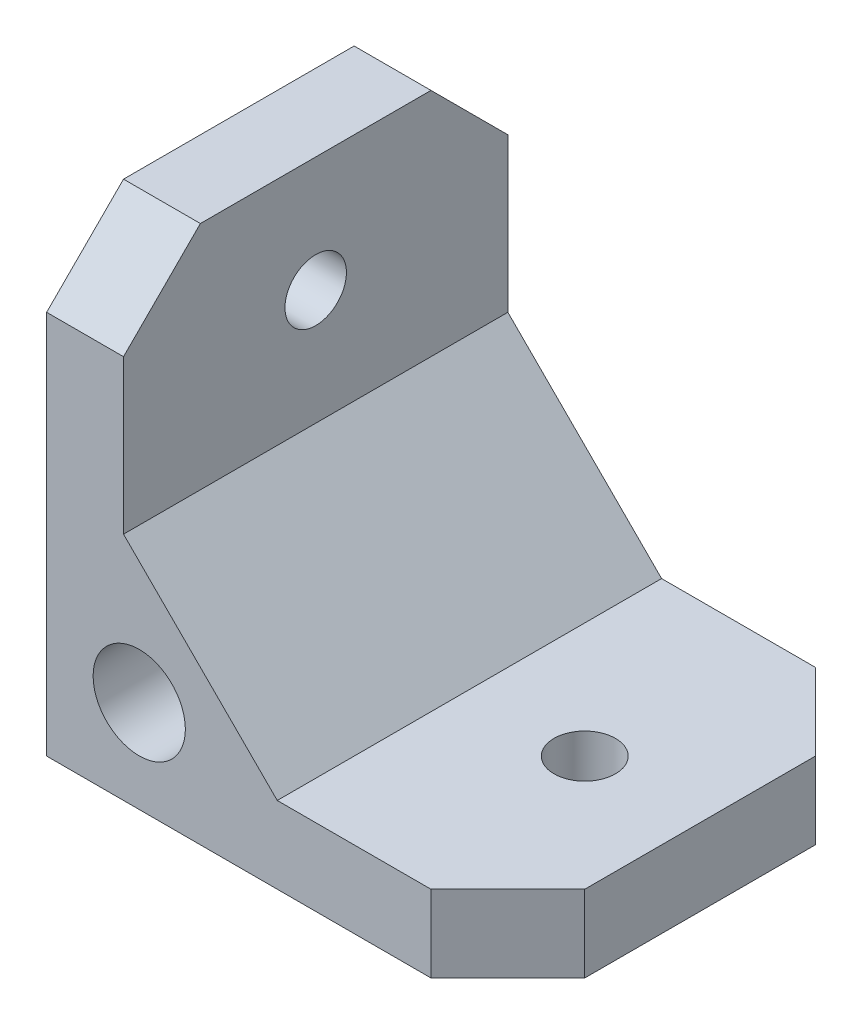
SolidWorks part; units mm, degrees
ref_plane "Front Plane" through (0, 0, 0) normal (0, 0, 1) x (1, 0, 0)
ref_plane "Top Plane" through (0, 0, 0) normal (0, 1, 0) x (1, 0, 0)
ref_plane "Right Plane" through (0, 0, 0) normal (1, 0, 0) x (0, 0, -1)
sketch "Sketch1" plane through (0, 0, 0) normal (0, 1, 0) x (1, 0, 0)
  line L1 (0, 0) -> (24, 0)
  line L2 (0, 0) -> (0, 20)
  line L3 (0, 20) -> (24, 20)
  line L4 (24, 0) -> (24, 20)
  dimension "D1" = 24
  dimension "D2" = 20
extrude "Boss-Extrude1" add sketch "Sketch1" along normal blind 4
sketch "Sketch2" plane through (0, 4, 0) normal (0, 1, 0) x (1, 0, 0)
  line L0 (0, 0) -> (24, 0) construction
  line L1 (0, 20) -> (4, 20)
  line L2 (0, 20) -> (0, 0)
  line L3 (0, 0) -> (4, 0)
  line L4 (4, 20) -> (4, 0)
  dimension "D1" = 4
extrude "Boss-Extrude2" add sketch "Sketch2" along normal blind 20
chamfer "Chamfer1" distance 8 angle 45 1 edges at (4, 4, -10)
sketch "Sketch3" plane through (0, 4, 0) normal (0, 1, 0) x (1, 0, 0)
  line L0 (12, 10) -> (24, 10) construction
  line L1 (12, 20) -> (12, 0) construction
  line L2 (24, 0) -> (24, 20) construction
  circle A0 centre (18, 10) radius 1.6
  dimension "D1" = 3.2
extrude "Cut-Extrude1" cut sketch "Sketch3" against normal blind 20
sketch "Sketch4" plane through (4, 0, 0) normal (1, 0, 0) x (0, 0, -1)
  line L0 (10, 24) -> (10, 12) construction
  line L1 (0, 24) -> (20, 24) construction
  line L2 (0, 12) -> (20, 12) construction
  circle A0 centre (10, 18) radius 1.6
  dimension "D1" = 3.2
extrude "Cut-Extrude2" cut sketch "Sketch4" against normal blind 20
chamfer "Chamfer2" distance 4 angle 45 4 edges at (24, 2, -20) (24, 2, 0) (2, 24, -20) (2, 24, 0)
sketch "Sketch5" plane through (0, 0, 0) normal (0, 0, 1) x (1, 0, 0)
  line L0 (8, 8) -> (0, 0) construction
  line L1 (12, 4) -> (4, 12) construction
  circle A0 centre (4.818, 4.818) radius 2.4
  dimension "D1" = 4.8
  dimension "D2" = 4.5
extrude "Cut-Extrude3" cut sketch "Sketch5" against normal through all both and the other way through all
